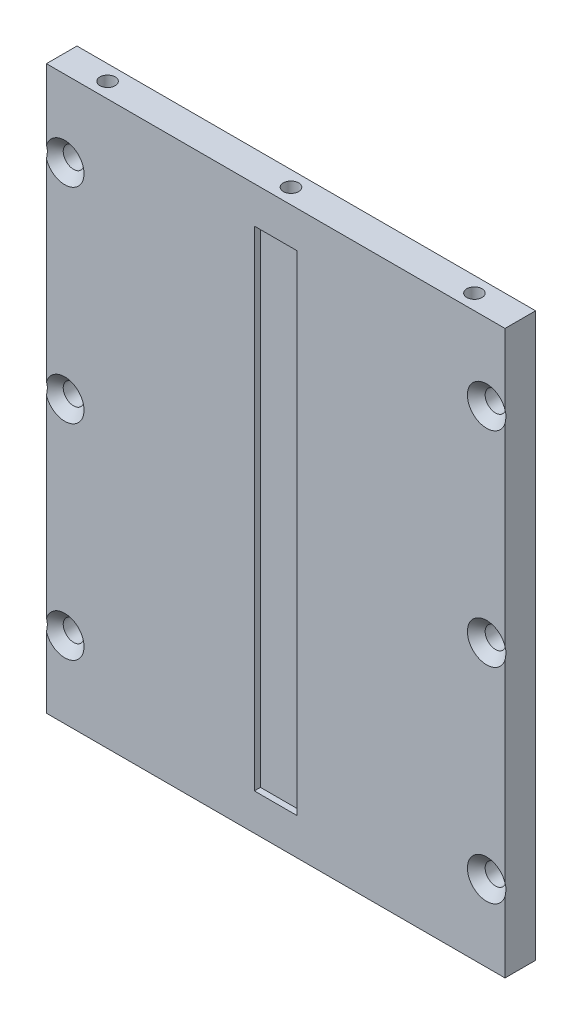
SolidWorks part; units mm, degrees
material "POM Ацеталь кополимер"
ref_plane "Front" through (0, 0, 0) normal (0, 0, 1) x (1, 0, 0)
ref_plane "Top" through (0, 0, 0) normal (0, 1, 0) x (1, 0, 0)
ref_plane "Right" through (0, 0, 0) normal (1, 0, 0) x (0, 0, -1)
sketch "Эскиз1" plane through (0, 0, 0) normal (0, 0, 1) x (1, 0, 0)
  line L1 (-37.5, 46) -> (37.5, 46)
  line L2 (-37.5, 46) -> (-37.5, -46)
  line L3 (-37.5, -46) -> (37.5, -46)
  line L4 (37.5, 46) -> (37.5, -46)
  line L5 (-37.5, 46) -> (37.5, -46) construction
  line L6 (-37.5, -46) -> (37.5, 46) construction
  point P0 (0, 0)
  dimension "D1" = 75
  dimension "D2" = 92
extrude "База" add sketch "Эскиз1" against normal blind 5
hole_wizard "Крепление M3" positions "Эскиз2" profile "Эскиз3" tap size "M3" standard "ISO" end condition through all
sketch "Эскиз2" plane through (0, 46, 0) normal (0, 1, 0) x (1, 0, 0)
  line L0 (-30, 2.5) -> (0, 2.5) construction
  line L1 (0, 2.5) -> (30, 2.5) construction
  line L4 (-37.5, 5) -> (-37.5, 0) construction
  line L5 (37.5, 5) -> (37.5, 0) construction
  point P0 (30, 2.5)
  point P3 (-30, 2.5)
  point P19 (-37.5, 2.5)
  point P22 (37.5, 2.5)
  point P25 (0, 2.5)
  dimension "D1" = 60
sketch "Эскиз3" plane through (30, 46, -2.5) normal (1, 0, 0) x (0, 0, 1)
  line L0 (0, 0) -> (0, 92)
  line L1 (0, 92) -> (1.25, 92)
  line L2 (1.25, 92) -> (1.25, 0)
  line L5 (1.25, 0) -> (0, 0)
  line L11 (0, -6.35) -> (0, 107.95) construction
  dimension "Диаметр проходного сверла" = 2.5
  dimension "Глубина проходного сверла" = 92
cosmetic thread "Отверстие резьбы1" parameters "D2"=3
cosmetic thread "Отверстие резьбы2" parameters "D2"=3
cosmetic thread "Отверстие резьбы3" parameters "D2"=3
hole_wizard "Зенковка M3" positions "Эскиз4" profile "Эскиз5" countersink size "M3" standard "ISO" end condition through all
sketch "Эскиз4" plane through (45, 0, 0) normal (0, 0, -1) x (-1, 0, 0)
  line L0 (10.5, 33.5) -> (10.5, 0) construction
  line L1 (10.5, 0) -> (10.5, -33.5) construction
  line L6 (10.5, 0) -> (7.5, 0) construction
  line L7 (7.5, -46) -> (7.5, 46) construction
  line L10 (79.5, 0) -> (82.5, 0) construction
  line L11 (82.5, 46) -> (82.5, -46) construction
  point P0 (10.5, 0)
  point P2 (10.5, 33.5)
  point P4 (10.5, -33.5)
  point P31 (79.5, 33.5)
  point P33 (79.5, 0)
  point P35 (79.5, -33.5)
  dimension "D1" = 67
  dimension "D2" = 3
sketch "Эскиз5" plane through (34.5, 0, 0) normal (1, 0, 0) x (0, -1, 0)
  line L0 (0, 0) -> (0, 5)
  line L1 (0, 5) -> (1.7, 5)
  line L2 (1.7, 5) -> (1.7, 1.45)
  line L3 (1.7, 1.45) -> (3.15, 0)
  line L5 (3.15, 0) -> (0, 0)
  line L6 (-1.7, 1.45) -> (-3.15, 0) construction
  line L11 (0, -6.35) -> (0, 107.95) construction
  dimension "Диаметр сквозного отверстия" = 3.4
  dimension "Глубина сквозного отверстия" = 5
  dimension "Диаметр передней зенковки" = 6.3
  dimension "Угол передней зенковки" = 90
sketch "Эскиз6" plane through (0, 0, 0) normal (0, 0, 1) x (1, 0, 0)
  line L1 (-3.5, 40) -> (3.5, 40)
  line L2 (-3.5, 40) -> (-3.5, -40)
  line L3 (-3.5, -40) -> (3.5, -40)
  line L4 (3.5, 40) -> (3.5, -40)
  line L5 (-3.5, 40) -> (3.5, -40) construction
  line L6 (-3.5, -40) -> (3.5, 40) construction
  point P0 (0, 0)
  dimension "D1" = 7
  dimension "D2" = 80
extrude "Вырез-Вытянуть1" cut sketch "Эскиз6" against normal blind 1
